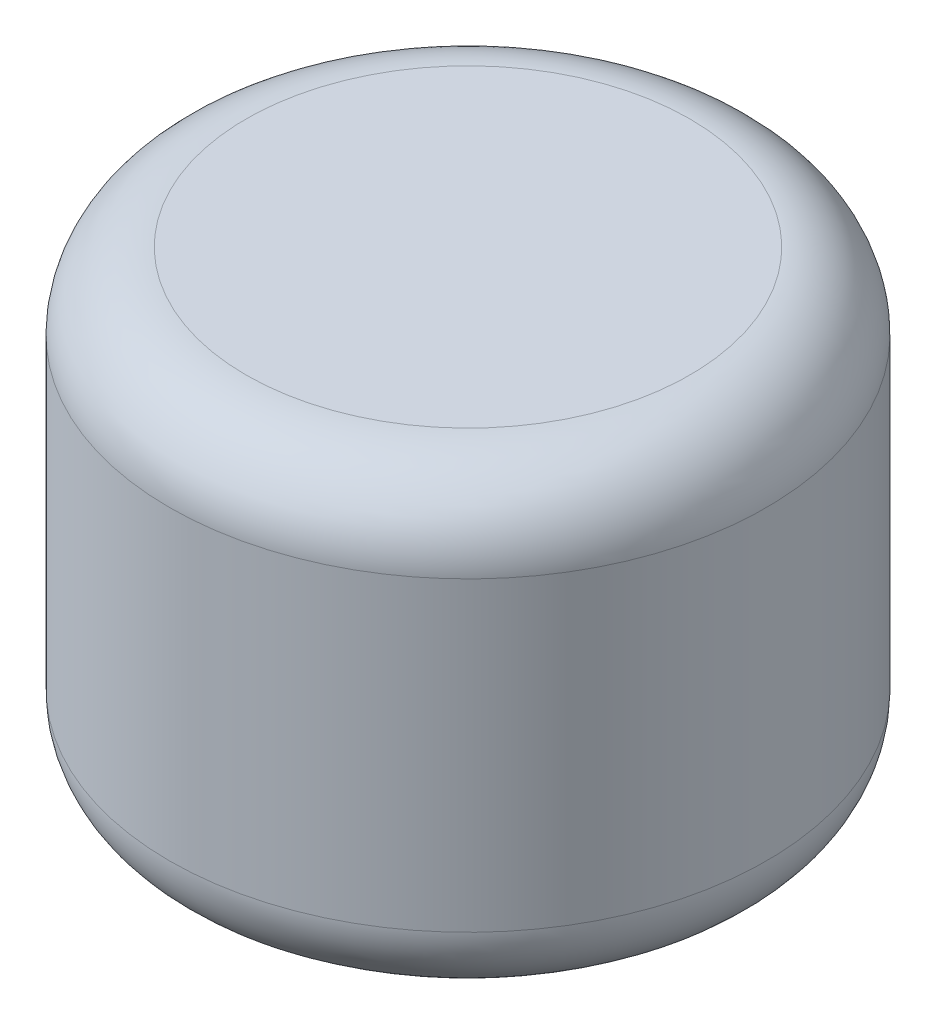
SolidWorks part; units mm, degrees
ref_plane "Front Plane" through (0, 0, 0) normal (0, 0, 1) x (1, 0, 0)
ref_plane "Top Plane" through (0, 0, 0) normal (0, 1, 0) x (1, 0, 0)
ref_plane "Right Plane" through (0, 0, 0) normal (1, 0, 0) x (0, 0, -1)
sketch "Sketch1" plane through (0, 0, 0) normal (0, 1, 0) x (1, 0, 0)
  circle A0 centre (0, 0) radius 49.53
  dimension "D1" = 99.06
extrude "Boss-Extrude1" add sketch "Sketch1" along normal blind 76.2 contours A0
fillet "Fillet1" radius 12.7 2 edges at (0, 0, 49.53) (0, 76.2, 49.53)
